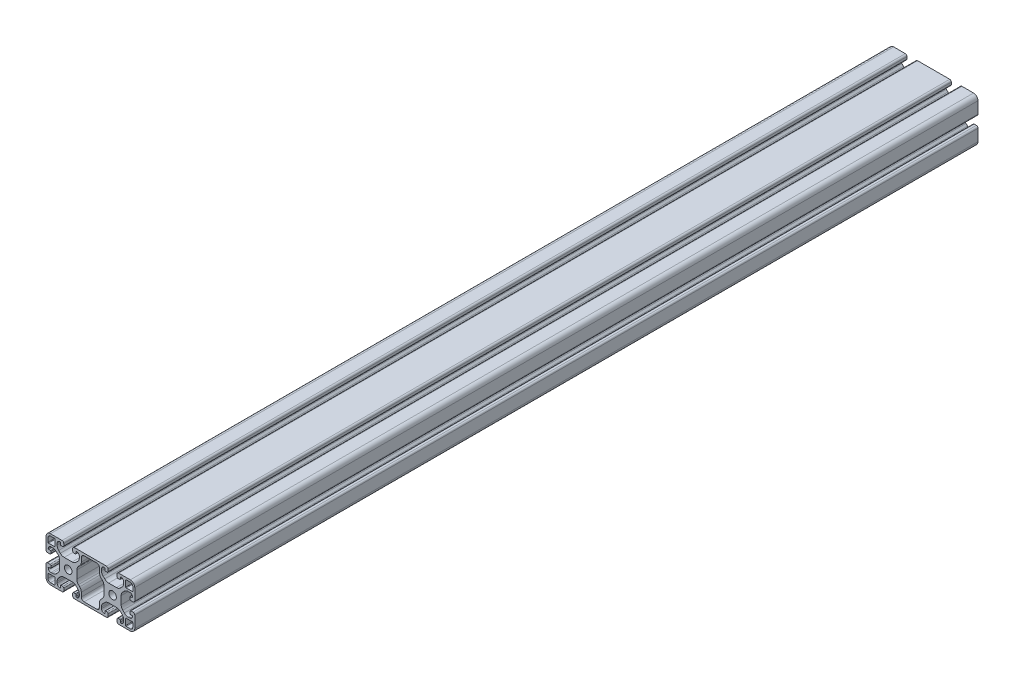
SolidWorks part; units mm, degrees
ref_plane "Plan de face" through (0, 0, 0) normal (0, 0, 1) x (1, 0, 0)
ref_plane "Plan de dessus" through (0, 0, 0) normal (0, 1, 0) x (1, 0, 0)
ref_plane "Plan de droite" through (0, 0, 0) normal (1, 0, 0) x (0, 0, -1)
ref_plane "Plan1" through (0, 0, 20) normal (0, 0, 1) x (1, 0, 0)
sketch "Esquisse1" plane through (0, 0, 20) normal (0, 0, 1) x (1, 0, 0)
  line L0 (66.5, 4.5) -> (65, 4.5)
  line L1 (64, 3.5) -> (64, 1.5)
  line L2 (65.5, 0) -> (76, 0)
  line L3 (80, 4) -> (80, 14.5)
  line L4 (78.5, 16) -> (76.5, 16)
  line L5 (75.5, 15) -> (75.5, 13.5)
  line L6 (76, 13) -> (77.5, 13)
  line L7 (75.5, 10) -> (74.1924, 10)
  line L8 (70.6569, 11.4645) -> (69.2145, 12.9069)
  line L9 (67.75, 16.4424) -> (67.75, 23.5576)
  line L10 (69.2145, 27.0931) -> (70.6569, 28.5355)
  line L11 (74.1924, 30) -> (75.5, 30)
  line L12 (77.5, 27) -> (76, 27)
  line L13 (75.5, 26.5) -> (75.5, 25)
  line L14 (76.5, 24) -> (78.5, 24)
  line L15 (80, 25.5) -> (80, 36)
  line L16 (76, 40) -> (65.5, 40)
  line L17 (64, 38.5) -> (64, 36.5)
  line L18 (65, 35.5) -> (66.5, 35.5)
  line L19 (67, 36) -> (67, 37.5)
  line L20 (70, 35.5) -> (70, 34.1924)
  line L21 (68.5355, 30.6569) -> (67.0931, 29.2145)
  line L22 (63.5576, 27.75) -> (56.4424, 27.75)
  line L23 (52.9069, 29.2145) -> (51.4645, 30.6569)
  line L24 (50, 34.1924) -> (50, 35.5)
  line L25 (53, 37.5) -> (53, 36)
  line L26 (53.5, 35.5) -> (55, 35.5)
  line L27 (56, 36.5) -> (56, 38.5)
  line L28 (54.5, 40) -> (25.5, 40)
  line L29 (24, 38.5) -> (24, 36.5)
  line L30 (25, 35.5) -> (26.5, 35.5)
  line L31 (27, 36) -> (27, 37.5)
  line L32 (30, 35.5) -> (30, 34.1924)
  line L33 (28.5355, 30.6569) -> (27.0931, 29.2145)
  line L34 (23.5576, 27.75) -> (16.4424, 27.75)
  line L35 (12.9069, 29.2145) -> (11.4645, 30.6569)
  line L36 (10, 34.1924) -> (10, 35.5)
  line L37 (13, 37.5) -> (13, 36)
  line L38 (13.5, 35.5) -> (15, 35.5)
  line L39 (16, 36.5) -> (16, 38.5)
  line L40 (14.5, 40) -> (4, 40)
  line L41 (0, 36) -> (0, 25.5)
  line L42 (1.5, 24) -> (3.5, 24)
  line L43 (4.5, 25) -> (4.5, 26.5)
  line L44 (4, 27) -> (2.5, 27)
  line L45 (4.5, 30) -> (5.8076, 30)
  line L46 (9.3431, 28.5355) -> (10.7855, 27.0931)
  line L47 (12.25, 23.5576) -> (12.25, 16.4424)
  line L48 (10.7855, 12.9069) -> (9.3431, 11.4645)
  line L49 (5.8076, 10) -> (4.5, 10)
  line L50 (2.5, 13) -> (4, 13)
  line L51 (4.5, 13.5) -> (4.5, 15)
  line L52 (3.5, 16) -> (1.5, 16)
  line L53 (0, 14.5) -> (0, 4)
  line L54 (4, 0) -> (14.5, 0)
  line L55 (16, 1.5) -> (16, 3.5)
  line L56 (15, 4.5) -> (13.5, 4.5)
  line L57 (13, 4) -> (13, 2.5)
  line L58 (10, 4.5) -> (10, 5.8076)
  line L59 (11.4645, 9.3431) -> (12.9069, 10.7855)
  line L60 (16.4424, 12.25) -> (23.5576, 12.25)
  line L61 (27.0931, 10.7855) -> (28.5355, 9.3431)
  line L62 (30, 5.8076) -> (30, 4.5)
  line L63 (27, 2.5) -> (27, 4)
  line L64 (26.5, 4.5) -> (25, 4.5)
  line L65 (24, 3.5) -> (24, 1.5)
  line L66 (25.5, 0) -> (54.5, 0)
  line L67 (56, 1.5) -> (56, 3.5)
  line L68 (55, 4.5) -> (53.5, 4.5)
  line L69 (53, 4) -> (53, 2.5)
  line L70 (50, 4.5) -> (50, 5.8076)
  line L71 (51.4645, 9.3431) -> (52.9069, 10.7855)
  line L72 (56.4424, 12.25) -> (63.5576, 12.25)
  line L73 (67.0931, 10.7855) -> (68.5355, 9.3431)
  line L74 (70, 5.8076) -> (70, 4.5)
  line L75 (67, 2.5) -> (67, 4)
  line L76 (31.8, 4.5) -> (31.8, 8.2503)
  line L77 (30.3355, 11.7858) -> (29.2145, 12.9069)
  line L78 (27.75, 16.4424) -> (27.75, 23.5576)
  line L79 (29.2145, 27.0931) -> (30.3355, 28.2142)
  line L80 (31.8, 31.7497) -> (31.8, 35.5)
  line L81 (34.3, 38) -> (45.7, 38)
  line L82 (48.2, 35.5) -> (48.2, 31.7497)
  line L83 (49.6645, 28.2142) -> (50.7855, 27.0931)
  line L84 (52.25, 23.5576) -> (52.25, 16.4424)
  line L85 (50.7855, 12.9069) -> (49.6645, 11.7858)
  line L86 (48.2, 8.2503) -> (48.2, 4.5)
  line L87 (45.7, 2) -> (34.3, 2)
  line L88 (7.7, 1.8) -> (4, 1.8)
  line L89 (1.8, 4) -> (1.8, 7.7)
  line L90 (2.3, 8.2) -> (7.7, 8.2)
  line L91 (8.2, 7.7) -> (8.2, 2.3)
  line L92 (72.3, 38.2) -> (76, 38.2)
  line L93 (78.2, 36) -> (78.2, 32.3)
  line L94 (77.7, 31.8) -> (72.3, 31.8)
  line L95 (71.8, 32.3) -> (71.8, 37.7)
  line L96 (78.2, 7.7) -> (78.2, 4)
  line L97 (76, 1.8) -> (72.3, 1.8)
  line L98 (71.8, 2.3) -> (71.8, 7.7)
  line L99 (72.3, 8.2) -> (77.7, 8.2)
  line L100 (1.8, 32.3) -> (1.8, 36)
  line L101 (4, 38.2) -> (7.7, 38.2)
  line L102 (8.2, 37.7) -> (8.2, 32.3)
  line L103 (7.7, 31.8) -> (2.3, 31.8)
  arc A0 (67, 4) -> (66.5, 4.5) centre (66.5, 4) ccw
  arc A1 (65, 4.5) -> (64, 3.5) centre (65, 3.5) ccw
  arc A2 (64, 1.5) -> (65.5, 0) centre (65.5, 1.5) ccw
  arc A3 (76, 0) -> (80, 4) centre (76, 4) ccw
  arc A4 (80, 14.5) -> (78.5, 16) centre (78.5, 14.5) ccw
  arc A5 (76.5, 16) -> (75.5, 15) centre (76.5, 15) ccw
  arc A6 (75.5, 13.5) -> (76, 13) centre (76, 13.5) ccw
  arc A7 (77.5, 13) -> (78, 12.5) centre (77.5, 12.5) cw
  arc A8 (78, 12.5) -> (75.5, 10) centre (75.5, 12.5) cw
  arc A9 (74.1924, 10) -> (70.6569, 11.4645) centre (74.1924, 15) cw
  arc A10 (69.2145, 12.9069) -> (67.75, 16.4424) centre (72.75, 16.4424) cw
  arc A11 (67.75, 23.5576) -> (69.2145, 27.0931) centre (72.75, 23.5576) cw
  arc A12 (70.6569, 28.5355) -> (74.1924, 30) centre (74.1924, 25) cw
  arc A13 (75.5, 30) -> (78, 27.5) centre (75.5, 27.5) cw
  arc A14 (78, 27.5) -> (77.5, 27) centre (77.5, 27.5) cw
  arc A15 (76, 27) -> (75.5, 26.5) centre (76, 26.5) ccw
  arc A16 (75.5, 25) -> (76.5, 24) centre (76.5, 25) ccw
  arc A17 (78.5, 24) -> (80, 25.5) centre (78.5, 25.5) ccw
  arc A18 (80, 36) -> (76, 40) centre (76, 36) ccw
  arc A19 (65.5, 40) -> (64, 38.5) centre (65.5, 38.5) ccw
  arc A20 (64, 36.5) -> (65, 35.5) centre (65, 36.5) ccw
  arc A21 (66.5, 35.5) -> (67, 36) centre (66.5, 36) ccw
  arc A22 (67, 37.5) -> (67.5, 38) centre (67.5, 37.5) cw
  arc A23 (67.5, 38) -> (70, 35.5) centre (67.5, 35.5) cw
  arc A24 (70, 34.1924) -> (68.5355, 30.6569) centre (65, 34.1924) cw
  arc A25 (67.0931, 29.2145) -> (63.5576, 27.75) centre (63.5576, 32.75) cw
  arc A26 (56.4424, 27.75) -> (52.9069, 29.2145) centre (56.4424, 32.75) cw
  arc A27 (51.4645, 30.6569) -> (50, 34.1924) centre (55, 34.1924) cw
  arc A28 (50, 35.5) -> (52.5, 38) centre (52.5, 35.5) cw
  arc A29 (52.5, 38) -> (53, 37.5) centre (52.5, 37.5) cw
  arc A30 (53, 36) -> (53.5, 35.5) centre (53.5, 36) ccw
  arc A31 (55, 35.5) -> (56, 36.5) centre (55, 36.5) ccw
  arc A32 (56, 38.5) -> (54.5, 40) centre (54.5, 38.5) ccw
  arc A33 (25.5, 40) -> (24, 38.5) centre (25.5, 38.5) ccw
  arc A34 (24, 36.5) -> (25, 35.5) centre (25, 36.5) ccw
  arc A35 (26.5, 35.5) -> (27, 36) centre (26.5, 36) ccw
  arc A36 (27, 37.5) -> (27.5, 38) centre (27.5, 37.5) cw
  arc A37 (27.5, 38) -> (30, 35.5) centre (27.5, 35.5) cw
  arc A38 (30, 34.1924) -> (28.5355, 30.6569) centre (25, 34.1924) cw
  arc A39 (27.0931, 29.2145) -> (23.5576, 27.75) centre (23.5576, 32.75) cw
  arc A40 (16.4424, 27.75) -> (12.9069, 29.2145) centre (16.4424, 32.75) cw
  arc A41 (11.4645, 30.6569) -> (10, 34.1924) centre (15, 34.1924) cw
  arc A42 (10, 35.5) -> (12.5, 38) centre (12.5, 35.5) cw
  arc A43 (12.5, 38) -> (13, 37.5) centre (12.5, 37.5) cw
  arc A44 (13, 36) -> (13.5, 35.5) centre (13.5, 36) ccw
  arc A45 (15, 35.5) -> (16, 36.5) centre (15, 36.5) ccw
  arc A46 (16, 38.5) -> (14.5, 40) centre (14.5, 38.5) ccw
  arc A47 (4, 40) -> (0, 36) centre (4, 36) ccw
  arc A48 (0, 25.5) -> (1.5, 24) centre (1.5, 25.5) ccw
  arc A49 (3.5, 24) -> (4.5, 25) centre (3.5, 25) ccw
  arc A50 (4.5, 26.5) -> (4, 27) centre (4, 26.5) ccw
  arc A51 (2.5, 27) -> (2, 27.5) centre (2.5, 27.5) cw
  arc A52 (2, 27.5) -> (4.5, 30) centre (4.5, 27.5) cw
  arc A53 (5.8076, 30) -> (9.3431, 28.5355) centre (5.8076, 25) cw
  arc A54 (10.7855, 27.0931) -> (12.25, 23.5576) centre (7.25, 23.5576) cw
  arc A55 (12.25, 16.4424) -> (10.7855, 12.9069) centre (7.25, 16.4424) cw
  arc A56 (9.3431, 11.4645) -> (5.8076, 10) centre (5.8076, 15) cw
  arc A57 (4.5, 10) -> (2, 12.5) centre (4.5, 12.5) cw
  arc A58 (2, 12.5) -> (2.5, 13) centre (2.5, 12.5) cw
  arc A59 (4, 13) -> (4.5, 13.5) centre (4, 13.5) ccw
  arc A60 (4.5, 15) -> (3.5, 16) centre (3.5, 15) ccw
  arc A61 (1.5, 16) -> (0, 14.5) centre (1.5, 14.5) ccw
  arc A62 (0, 4) -> (4, 0) centre (4, 4) ccw
  arc A63 (14.5, 0) -> (16, 1.5) centre (14.5, 1.5) ccw
  arc A64 (16, 3.5) -> (15, 4.5) centre (15, 3.5) ccw
  arc A65 (13.5, 4.5) -> (13, 4) centre (13.5, 4) ccw
  arc A66 (13, 2.5) -> (12.5, 2) centre (12.5, 2.5) cw
  arc A67 (12.5, 2) -> (10, 4.5) centre (12.5, 4.5) cw
  arc A68 (10, 5.8076) -> (11.4645, 9.3431) centre (15, 5.8076) cw
  arc A69 (12.9069, 10.7855) -> (16.4424, 12.25) centre (16.4424, 7.25) cw
  arc A70 (23.5576, 12.25) -> (27.0931, 10.7855) centre (23.5576, 7.25) cw
  arc A71 (28.5355, 9.3431) -> (30, 5.8076) centre (25, 5.8076) cw
  arc A72 (30, 4.5) -> (27.5, 2) centre (27.5, 4.5) cw
  arc A73 (27.5, 2) -> (27, 2.5) centre (27.5, 2.5) cw
  arc A74 (27, 4) -> (26.5, 4.5) centre (26.5, 4) ccw
  arc A75 (25, 4.5) -> (24, 3.5) centre (25, 3.5) ccw
  arc A76 (24, 1.5) -> (25.5, 0) centre (25.5, 1.5) ccw
  arc A77 (54.5, 0) -> (56, 1.5) centre (54.5, 1.5) ccw
  arc A78 (56, 3.5) -> (55, 4.5) centre (55, 3.5) ccw
  arc A79 (53.5, 4.5) -> (53, 4) centre (53.5, 4) ccw
  arc A80 (53, 2.5) -> (52.5, 2) centre (52.5, 2.5) cw
  arc A81 (52.5, 2) -> (50, 4.5) centre (52.5, 4.5) cw
  arc A82 (50, 5.8076) -> (51.4645, 9.3431) centre (55, 5.8076) cw
  arc A83 (52.9069, 10.7855) -> (56.4424, 12.25) centre (56.4424, 7.25) cw
  arc A84 (63.5576, 12.25) -> (67.0931, 10.7855) centre (63.5576, 7.25) cw
  arc A85 (68.5355, 9.3431) -> (70, 5.8076) centre (65, 5.8076) cw
  arc A86 (70, 4.5) -> (67.5, 2) centre (67.5, 4.5) cw
  arc A87 (67.5, 2) -> (67, 2.5) centre (67.5, 2.5) cw
  circle A88 centre (20, 20) radius 3.4
  circle A89 centre (60, 20) radius 3.4
  arc A90 (34.3, 2) -> (31.8, 4.5) centre (34.3, 4.5) cw
  arc A91 (31.8, 8.2503) -> (30.3355, 11.7858) centre (26.8, 8.2503) ccw
  arc A92 (29.2145, 12.9069) -> (27.75, 16.4424) centre (32.75, 16.4424) cw
  arc A93 (27.75, 23.5576) -> (29.2145, 27.0931) centre (32.75, 23.5576) cw
  arc A94 (30.3355, 28.2142) -> (31.8, 31.7497) centre (26.8, 31.7497) ccw
  arc A95 (31.8, 35.5) -> (34.3, 38) centre (34.3, 35.5) cw
  arc A96 (45.7, 38) -> (48.2, 35.5) centre (45.7, 35.5) cw
  arc A97 (48.2, 31.7497) -> (49.6645, 28.2142) centre (53.2, 31.7497) ccw
  arc A98 (50.7855, 27.0931) -> (52.25, 23.5576) centre (47.25, 23.5576) cw
  arc A99 (52.25, 16.4424) -> (50.7855, 12.9069) centre (47.25, 16.4424) cw
  arc A100 (49.6645, 11.7858) -> (48.2, 8.2503) centre (53.2, 8.2503) ccw
  arc A101 (48.2, 4.5) -> (45.7, 2) centre (45.7, 4.5) cw
  arc A102 (8.2, 2.3) -> (7.7, 1.8) centre (7.7, 2.3) cw
  arc A103 (4, 1.8) -> (1.8, 4) centre (4, 4) cw
  arc A104 (1.8, 7.7) -> (2.3, 8.2) centre (2.3, 7.7) cw
  arc A105 (7.7, 8.2) -> (8.2, 7.7) centre (7.7, 7.7) cw
  arc A106 (71.8, 37.7) -> (72.3, 38.2) centre (72.3, 37.7) cw
  arc A107 (76, 38.2) -> (78.2, 36) centre (76, 36) cw
  arc A108 (78.2, 32.3) -> (77.7, 31.8) centre (77.7, 32.3) cw
  arc A109 (72.3, 31.8) -> (71.8, 32.3) centre (72.3, 32.3) cw
  arc A110 (77.7, 8.2) -> (78.2, 7.7) centre (77.7, 7.7) cw
  arc A111 (78.2, 4) -> (76, 1.8) centre (76, 4) cw
  arc A112 (72.3, 1.8) -> (71.8, 2.3) centre (72.3, 2.3) cw
  arc A113 (71.8, 7.7) -> (72.3, 8.2) centre (72.3, 7.7) cw
  arc A114 (2.3, 31.8) -> (1.8, 32.3) centre (2.3, 32.3) cw
  arc A115 (1.8, 36) -> (4, 38.2) centre (4, 36) cw
  arc A116 (7.7, 38.2) -> (8.2, 37.7) centre (7.7, 37.7) cw
  arc A117 (8.2, 32.3) -> (7.7, 31.8) centre (7.7, 32.3) cw
extrude "Boss.-Extru.1" add sketch "Esquisse1" against normal blind 760
